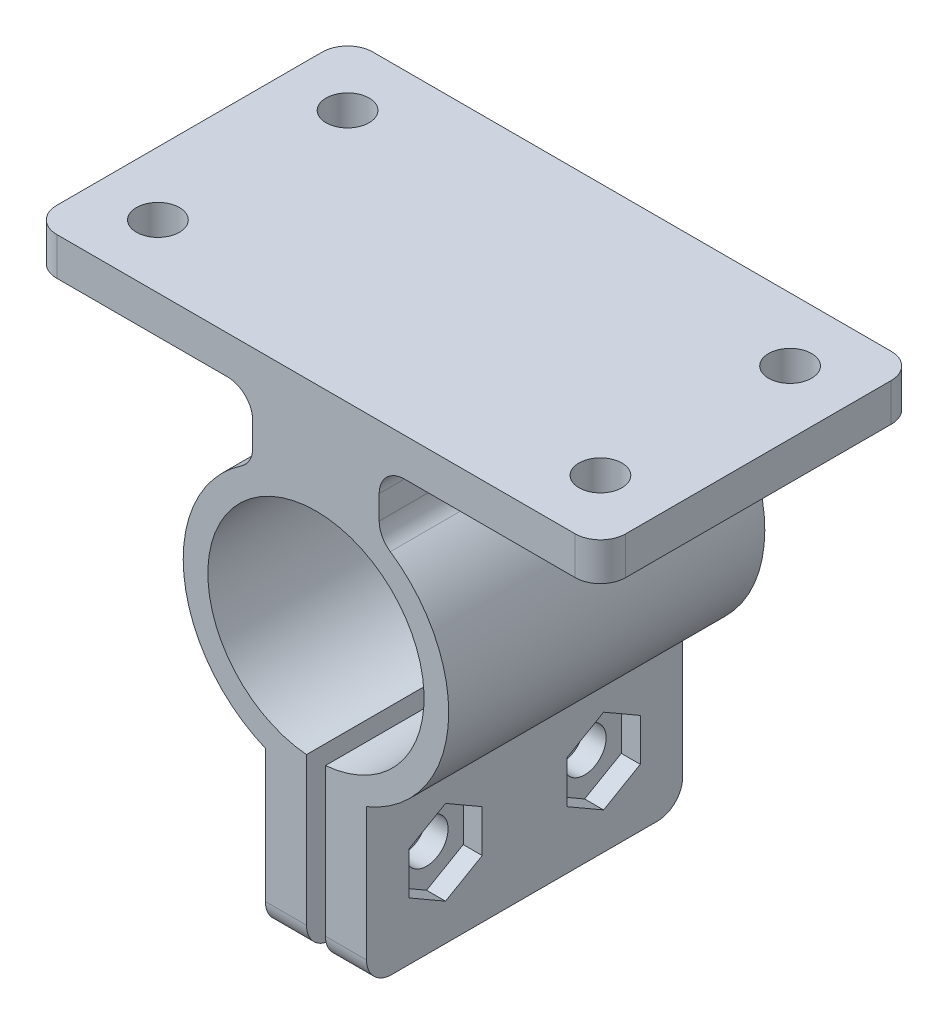
SolidWorks part; units mm, degrees
ref_plane "Front Plane" through (0, 0, 0) normal (0, 0, 1) x (1, 0, 0)
ref_plane "Top Plane" through (0, 0, 0) normal (0, 1, 0) x (1, 0, 0)
ref_plane "Right Plane" through (0, 0, 0) normal (1, 0, 0) x (0, 0, -1)
sketch "Sketch1" plane through (0, 0, 0) normal (0, 1, 0) x (1, 0, 0)
  line L1 (-22.5, 12.5) -> (22.5, 12.5)
  line L2 (-22.5, 12.5) -> (-22.5, -12.5)
  line L3 (-22.5, -12.5) -> (22.5, -12.5)
  line L4 (22.5, 12.5) -> (22.5, -12.5)
  line L5 (0, -12.5) -> (0, 12.5) construction
  line L6 (-22.5, 0) -> (22.5, 0) construction
  circle A0 centre (-17.5, 7.5) radius 1.7
  circle A1 centre (17.5, 7.5) radius 1.7
  circle A2 centre (17.5, -7.5) radius 1.7
  circle A3 centre (-17.5, -7.5) radius 1.7
  point P312 (0, 0)
  dimension "D3" = 3.4
  dimension "D6" = 5
  dimension "D1" = 45
  dimension "D2" = 25
  dimension "D7" = 5
  dimension "D4" = 2
  dimension "D5" = 2
extrude "Boss-Extrude1" add sketch "Sketch1" along normal blind 3
sketch "Sketch2" plane through (0, 0, 0) normal (0, -1, 0) x (1, 0, 0)
  line L0 (-22.5, 12.5) -> (22.5, 12.5) construction
  line L1 (-5, 12.5) -> (5, 12.5)
  line L2 (-5, 12.5) -> (-5, -12.5)
  line L3 (-5, -12.5) -> (5, -12.5)
  line L4 (5, 12.5) -> (5, -12.5)
  line L5 (0, -12.5) -> (0, 12.5) construction
  line L6 (-5, 0) -> (5, 0) construction
  line L7 (22.5, -12.5) -> (-22.5, -12.5) construction
  point P412 (0, 0)
  dimension "D1" = 10
extrude "Boss-Extrude2" add sketch "Sketch2" along normal blind 5
sketch "Sketch3" plane through (0, 0, 12.5) normal (0, 0, 1) x (1, 0, 0)
  line L0 (4, -23.9413) -> (4, -36.4413)
  line L1 (4, -36.4413) -> (-4, -36.4413)
  line L2 (-4, -36.4413) -> (-4, -23.9413)
  line L4 (5, -5) -> (-5, -5)
  arc A0 (-5, -5) -> (-4, -23.9413) centre (0, -14.2331) ccw
  arc A1 (4, -23.9413) -> (5, -5) centre (0, -14.2331) ccw
  point P7 (0, -36.4413)
  dimension "D1" = 21
  dimension "D2" = 8
  dimension "D3" = 12.5
extrude "Boss-Extrude3" add sketch "Sketch3" against normal up to surface (25 mm away) up to face at (0, -0.5, -12.5)
sketch "Sketch4" plane through (0, 0, 12.5) normal (0, 0, 1) x (1, 0, 0)
  line L0 (-4, -36.4413) -> (4, -36.4413) construction
  line L2 (-0.75, -22.7501) -> (-0.75, -36.4413)
  line L3 (-0.75, -36.4413) -> (0.75, -36.4413)
  line L4 (0.75, -22.7501) -> (0.75, -36.4413)
  line L5 (0, -36.4413) -> (0, -22.2175) construction
  line L6 (-0.75, -29.5957) -> (0.75, -29.5957) construction
  arc A0 (0.75, -22.7501) -> (-0.75, -22.7501) centre (0, -14.2331) ccw
  point P311 (0, -29.5957)
  dimension "D1" = 17.1
  dimension "D2" = 1.5
extrude "Cut-Extrude1" cut sketch "Sketch4" against normal through all
sketch "Sketch5" plane through (4, 0, 0) normal (1, 0, 0) x (0, 0, -1)
  line L0 (-12.5, -36.4413) -> (-12.5, -23.9413) construction
  line L2 (-6.25, -30.1913) -> (6.25, -30.1913) construction
  line L3 (12.5, -36.4413) -> (-12.5, -36.4413) construction
  circle A0 centre (-6.25, -30.1913) radius 1.7
  circle A1 centre (6.25, -30.1913) radius 1.7
  point P2 (0, -30.1913)
  point P5 (-12.5, -30.1913)
  point P10 (0, -36.4413)
  dimension "D2" = 3.4
  dimension "D3" = 12.5
  dimension "D1" = 2
extrude "Cut-Extrude2" cut sketch "Sketch5" against normal through all
sketch "Sketch6" plane through (4, 0, 0) normal (1, 0, 0) x (0, 0, -1)
  line L0 (9.15, -28.517) -> (6.25, -26.8427)
  line L1 (-3.35, -28.517) -> (-6.25, -26.8427)
  line L2 (-6.25, -26.8427) -> (-9.15, -28.517)
  line L3 (-9.15, -28.517) -> (-9.15, -31.8657)
  line L4 (-9.15, -31.8657) -> (-6.25, -33.54)
  line L5 (-6.25, -33.54) -> (-3.35, -31.8657)
  line L6 (-3.35, -31.8657) -> (-3.35, -28.517)
  line L7 (6.25, -26.8427) -> (3.35, -28.517)
  line L8 (3.35, -28.517) -> (3.35, -31.8657)
  line L9 (3.35, -31.8657) -> (6.25, -33.54)
  line L10 (6.25, -33.54) -> (9.15, -31.8657)
  line L11 (9.15, -31.8657) -> (9.15, -28.517)
  circle A0 centre (-6.25, -30.1913) radius 2.9 construction
  circle A1 centre (6.25, -30.1913) radius 2.9 construction
  dimension "D1" = 5.8
  dimension "D2" = 2
extrude "Cut-Extrude3" cut sketch "Sketch6" against normal blind 1.5
fillet "Fillet1" radius 2 4 edges at (-22.5, 1.5, -12.5) (-22.5, 1.5, 12.5) (22.5, 1.5, -12.5) (22.5, 1.5, 12.5)
fillet "Fillet2" radius 2 4 edges at (-5, 0, 0) (-5, -5, 0) (5, 0, 0) (5, -5, 0)
fillet "Fillet3" radius 2 4 edges at (-2.375, -36.4413, 12.5) (-2.375, -36.4413, -12.5) (2.375, -36.4413, -12.5) (2.375, -36.4413, 12.5)
